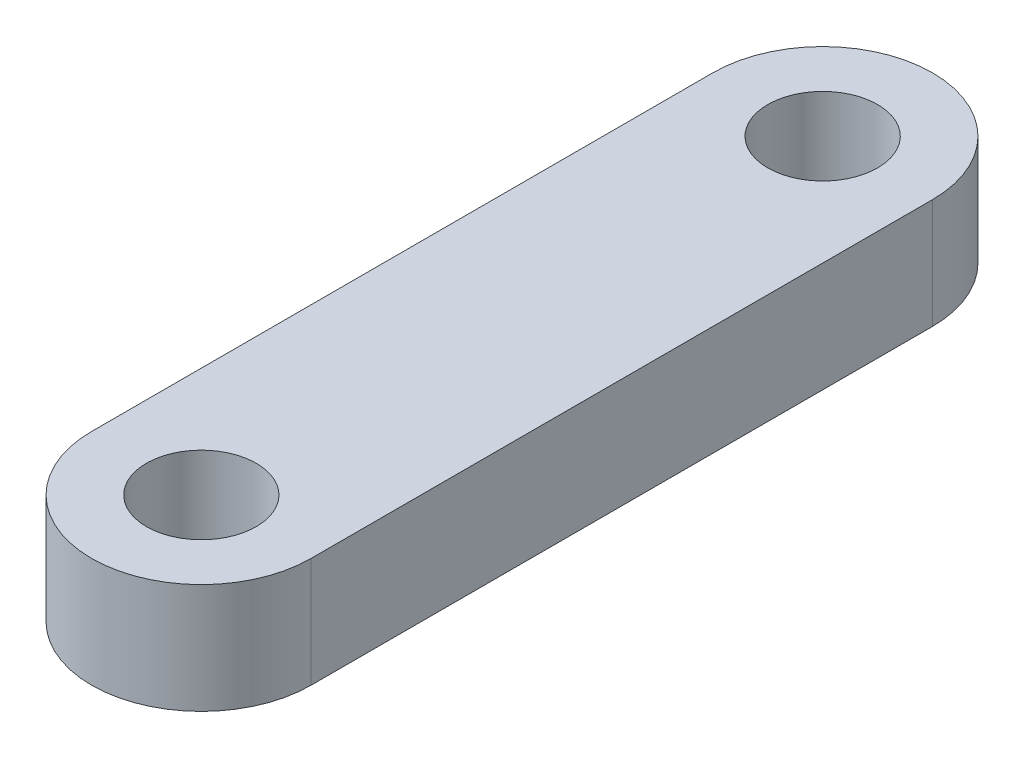
SolidWorks part; units mm, degrees
ref_plane "Front" through (0, 0, 0) normal (0, 0, 1) x (1, 0, 0)
ref_plane "Top" through (0, 0, 0) normal (0, 1, 0) x (1, 0, 0)
ref_plane "Right" through (0, 0, 0) normal (1, 0, 0) x (0, 0, -1)
sketch "Sketch1" plane through (0, 0, 0) normal (0, 1, 0) x (1, 0, 0)
  line L1 (-5, -14.1421) -> (5, -14.1421) construction
  line L2 (-5, -14.1421) -> (-5, 14.1421)
  line L3 (-5, 14.1421) -> (5, 14.1421) construction
  line L4 (5, -14.1421) -> (5, 14.1421)
  line L5 (-5, -14.1421) -> (5, 14.1421) construction
  line L6 (-5, 14.1421) -> (5, -14.1421) construction
  arc A0 (-5, 14.1421) -> (5, 14.1421) centre (0, 14.1421) cw
  arc A1 (-5, -14.1421) -> (5, -14.1421) centre (0, -14.1421) ccw
  point P0 (0, 0)
  dimension "D1" = 10
  dimension "D2" = 28.2843
extrude "Boss-Extrude1" add sketch "Sketch1" along normal blind 5
sketch "Sketch2" plane through (0, 5, 0) normal (0, 1, 0) x (1, 0, 0)
  circle A0 centre (0, 14.1421) radius 2.5
  circle A1 centre (0, -14.1421) radius 2.5
  dimension "D1" = 5
extrude "Cut-Extrude1" cut sketch "Sketch2" against normal through all
